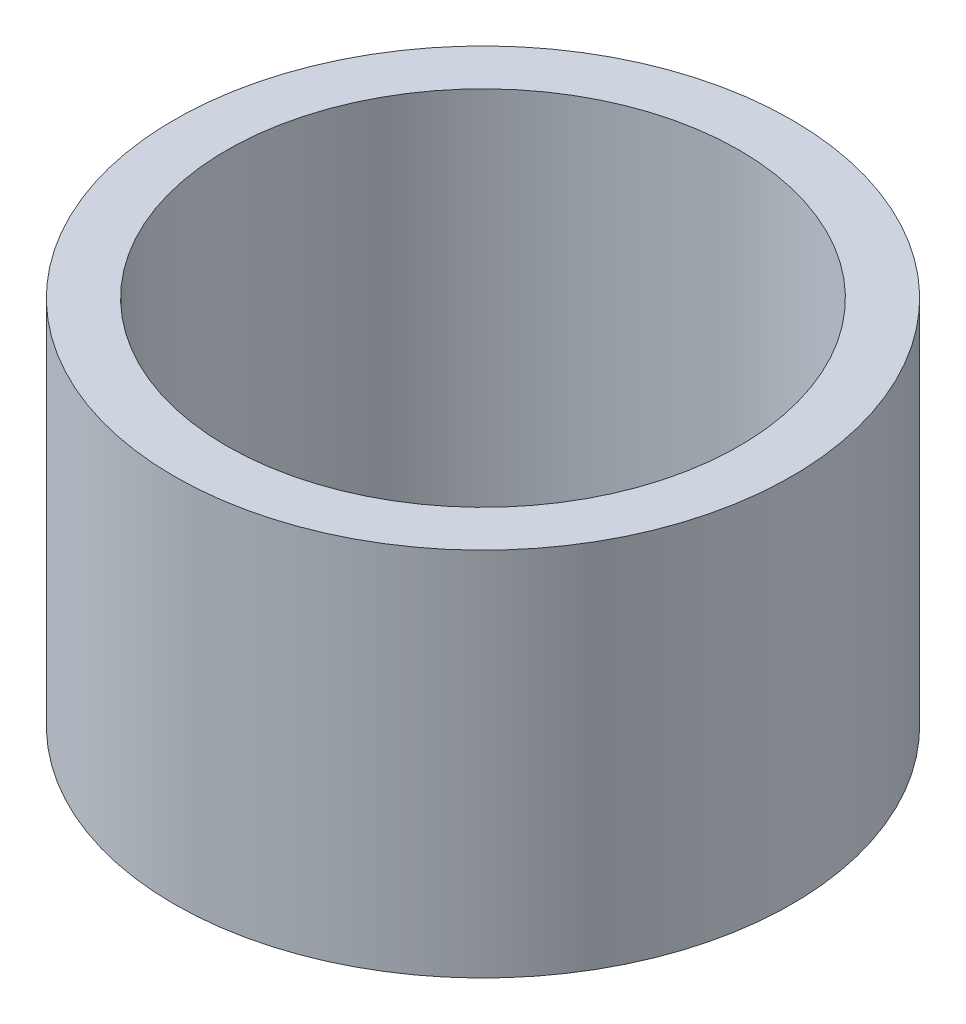
SolidWorks part; units mm, degrees
ref_plane "前视基准面" through (0, 0, 0) normal (0, 0, 1) x (1, 0, 0)
ref_plane "上视基准面" through (0, 0, 0) normal (0, 1, 0) x (1, 0, 0)
ref_plane "右视基准面" through (0, 0, 0) normal (1, 0, 0) x (0, 0, -1)
other "Configuration Table"
sketch "草图1" plane through (0, 0, 0) normal (0, 0, 1) x (1, 0, 0)
  line L0 (0, 0) -> (10, 0)
  line L1 (10, 0) -> (10, 12)
  line L2 (10, 12) -> (0, 12)
  line L3 (0, 12) -> (0, 0)
  line L4 (0, 0) -> (0, 12) construction
  dimension "radius" = 10
  dimension "height" = 12
revolve "Round_pushrod_head" add sketch "草图1" angle 360 about L4
sketch "草图2" plane through (0, 12, 0) normal (0, 1, 0) x (1, 0, 0)
  circle A0 centre (0, 0) radius 4.3
  dimension "diameter" = 8.6
extrude "Axial_bore" cut sketch "草图2" against normal through all
sketch "草图3" plane through (0, 12, 0) normal (0, 1, 0) x (1, 0, 0)
  circle A0 centre (0, 0) radius 8.3
  dimension "diameter" = 16.6
extrude "D16_clearance" cut sketch "草图3" against normal through all
